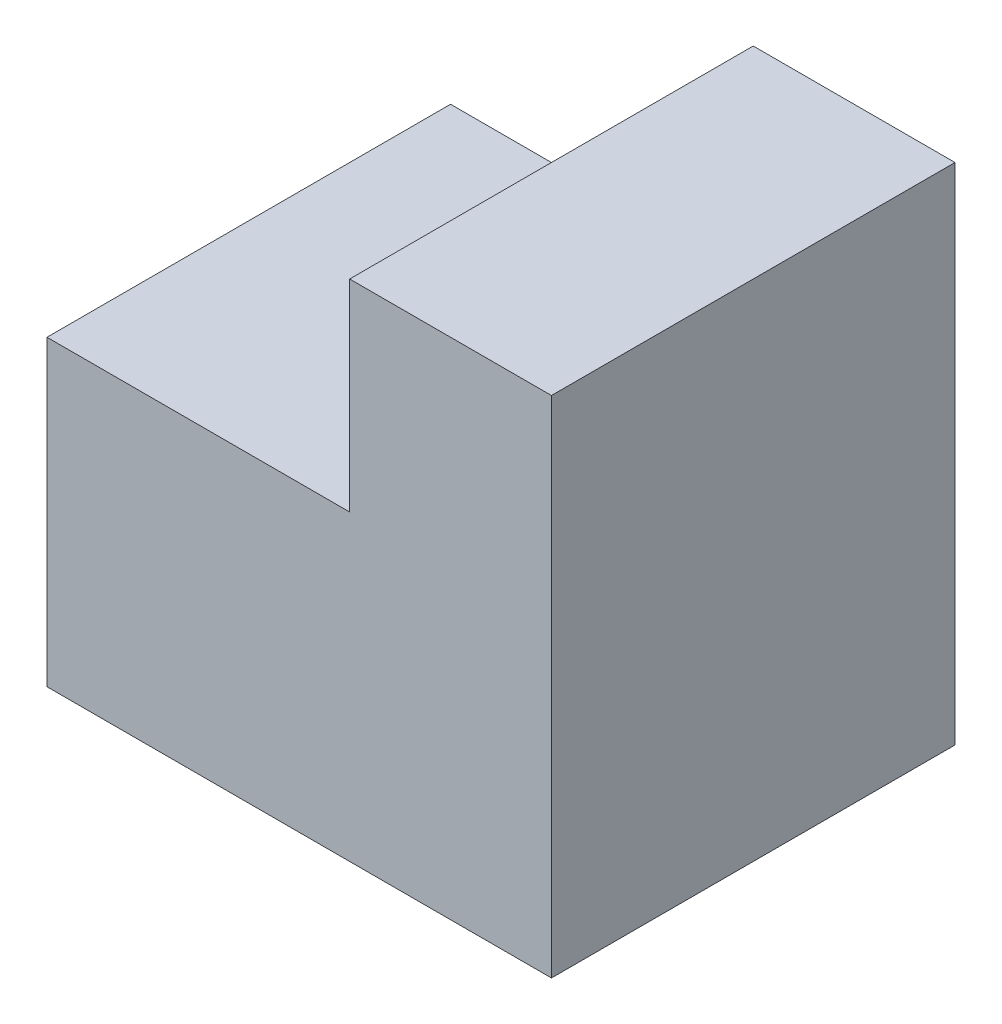
SolidWorks part; units mm, degrees
ref_plane "Front Plane" through (0, 0, 0) normal (0, 0, 1) x (1, 0, 0)
ref_plane "Top Plane" through (0, 0, 0) normal (0, 1, 0) x (1, 0, 0)
ref_plane "Right Plane" through (0, 0, 0) normal (1, 0, 0) x (0, 0, -1)
sketch "Sketch1" plane through (0, 0, 0) normal (0, 0, 1) x (1, 0, 0)
  line L0 (0, 0) -> (50, 0)
  line L1 (50, 0) -> (50, 50)
  line L2 (50, 50) -> (30, 50)
  line L3 (30, 50) -> (30, 30)
  line L4 (30, 30) -> (0, 30)
  line L5 (0, 30) -> (0, 0)
  point P6 (0, 0)
  dimension "D1" = 50
  dimension "D2" = 30
  dimension "D3" = 50
  dimension "D4" = 30
extrude "Boss-Extrude1" add sketch "Sketch1" against normal blind 40 contours L4 L5 L0 L1 L2 L3
